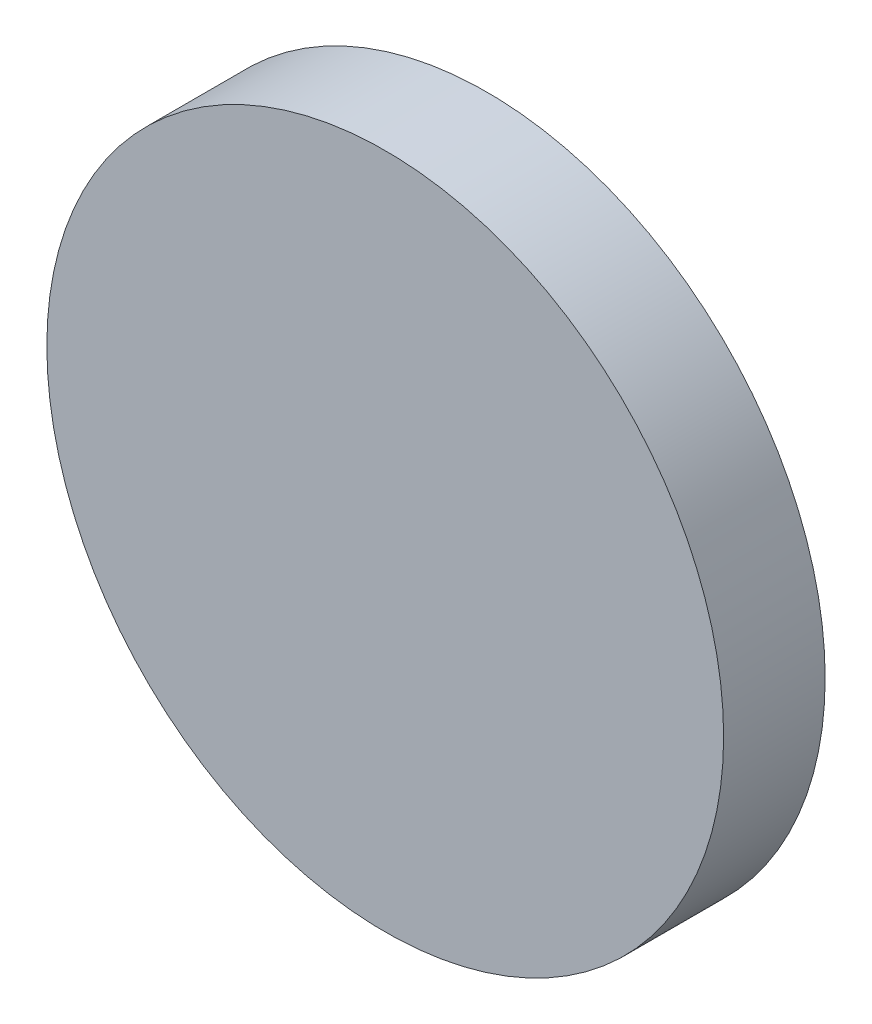
SolidWorks part; units mm, degrees
ref_plane "Front Plane" through (0, 0, 0) normal (0, 0, 1) x (1, 0, 0)
ref_plane "Top Plane" through (0, 0, 0) normal (0, 1, 0) x (1, 0, 0)
ref_plane "Right Plane" through (0, 0, 0) normal (1, 0, 0) x (0, 0, -1)
sketch "Sketch1" plane through (0, 0, 0) normal (0, 0, 1) x (1, 0, 0)
  circle A0 centre (0, 0) radius 100
  dimension "D1" = 200
extrude "Boss-Extrude1" add sketch "Sketch1" along normal blind 30
